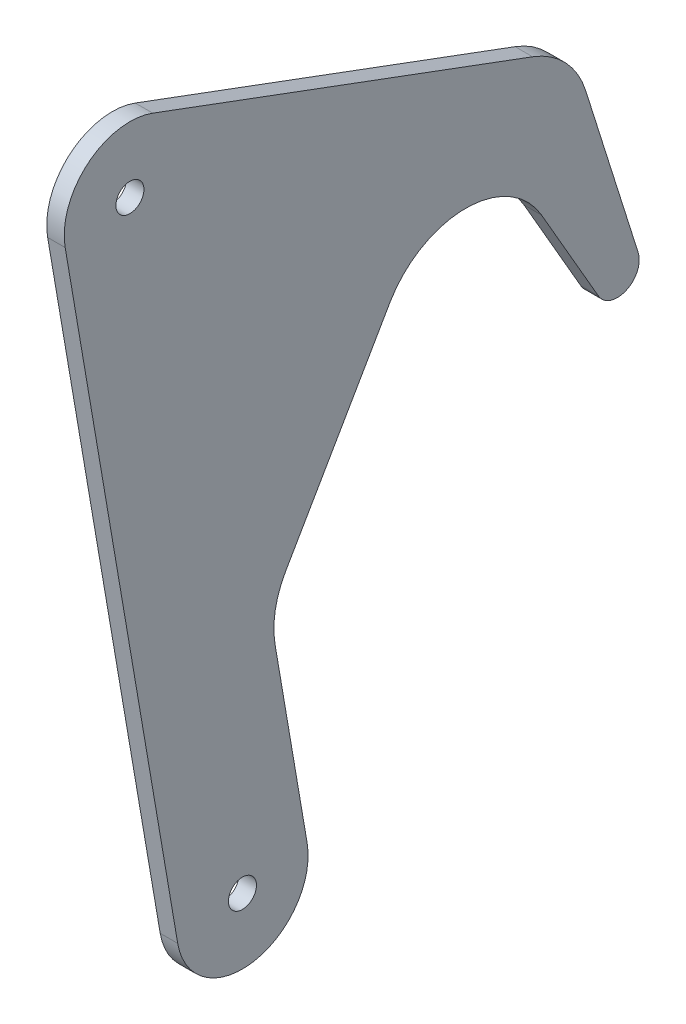
SolidWorks part; units mm, degrees
ref_plane "Front Plane" through (0, 0, 0) normal (0, 0, 1) x (1, 0, 0)
ref_plane "Top Plane" through (0, 0, 0) normal (0, 1, 0) x (1, 0, 0)
ref_plane "Right Plane" through (0, 0, 0) normal (1, 0, 0) x (0, 0, -1)
sketch "Sketch1" plane through (0, 0, 0) normal (1, 0, 0) x (0, 0, -1)
  line L0 (-25.7113, 93.9613) -> (-9.389, -1.6036)
  line L1 (-13.0053, 104.4937) -> (47.9145, 81.8631)
  line L2 (47.9145, 81.8631) -> (57.4077, 51.7547)
  line L3 (51.63, 49.2125) -> (43.3811, 63.5)
  line L5 (9.389, 1.6036) -> (4.7409, 28.8181)
  line L6 (6.2611, 37.3063) -> (21.384, 63.5)
  line L7 (29.7694, -209.55) -> (-337.2154, -209.55) construction
  arc A0 (-9.389, -1.6036) -> (9.389, 1.6036) centre (0, 0) ccw
  arc A1 (-13.0053, 104.4937) -> (-25.7113, 93.9613) centre (-16.3222, 95.5649) ccw
  arc A2 (57.4077, 51.7547) -> (51.63, 49.2125) centre (54.3796, 50.8) cw
  arc A3 (43.3811, 63.5) -> (21.384, 63.5) centre (32.3826, 57.15) ccw
  circle A4 centre (-16.3222, 95.5649) radius 2.032 construction
  arc A5 (6.2611, 37.3063) -> (4.7409, 28.8181) centre (17.2596, 30.9563) ccw
  point P18 (22.881, 48.8601)
  point P20 (32.3826, 69.85)
  point P23 (40.3582, 55.6995)
  point P24 (37.6086, 76.5071)
  point P25 (35.6911, 85.886)
  dimension "D1" = 19.05
  dimension "D2" = 12.7
  dimension "D3" = 3.175
  dimension "D6" = 30.2459
  dimension "D8" = 28.575
  dimension "D4" = 279.4
  dimension "D5" = 60
  dimension "D7" = 12.5
  dimension "D9" = 6.35
extrude "Boss-Extrude1" add sketch "Sketch1" along normal blind 2.54
sketch "Sketch2" plane through (2.54, 0, 0) normal (1, 0, 0) x (0, 0, -1)
  circle A0 centre (0, 0) radius 2.032
  circle A1 centre (-16.3222, 95.5649) radius 2.032
  arc A2 (-13.0053, 104.4937) -> (-25.7113, 93.9613) centre (-16.3222, 95.5649) ccw construction
  dimension "D1" = 4.064
extrude "Cut-Extrude1" cut sketch "Sketch2" against normal through all
fillet "Fillet1" radius 12.7 1 edges at (1.27, 81.8631, -47.9145)
